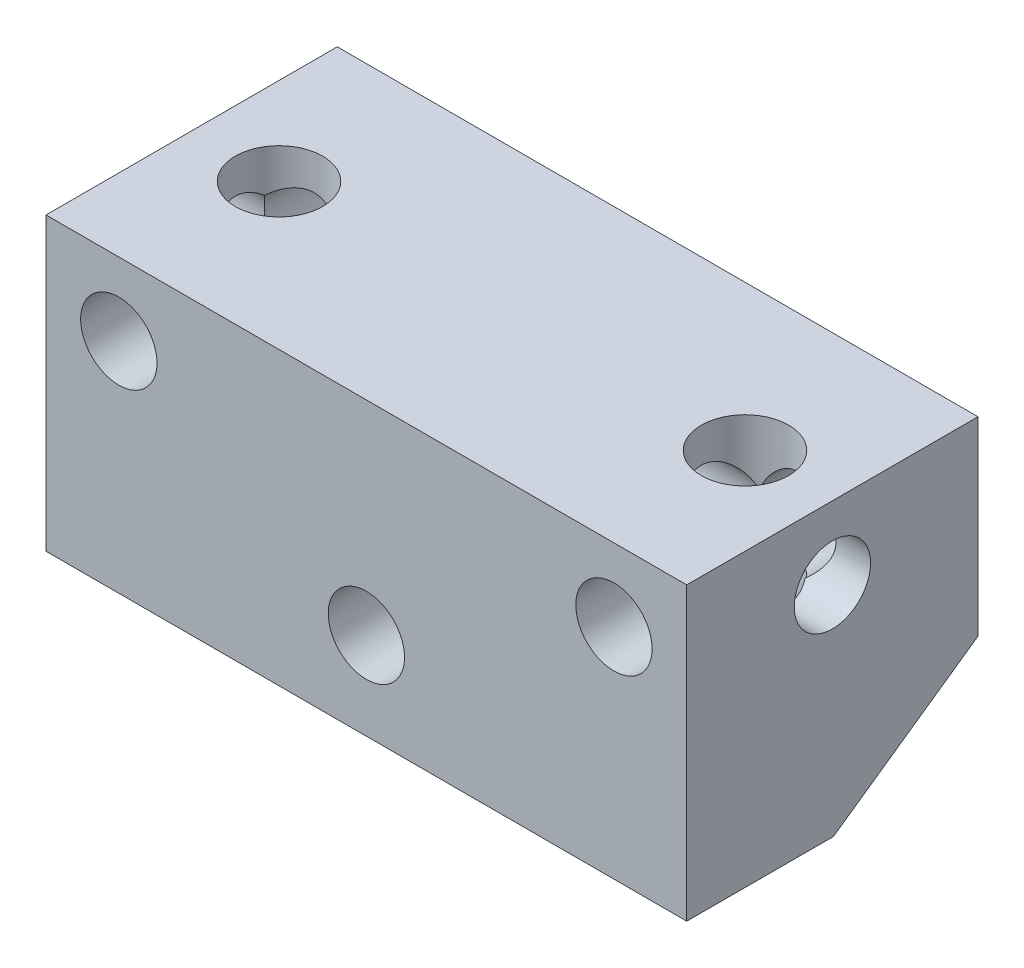
SolidWorks part; units mm, degrees
ref_plane "Front Plane" through (0, 0, 0) normal (0, 0, 1) x (1, 0, 0)
ref_plane "Top Plane" through (0, 0, 0) normal (0, 1, 0) x (1, 0, 0)
ref_plane "Right Plane" through (0, 0, 0) normal (1, 0, 0) x (0, 0, -1)
ref_plane "Plane1" through (11, 0, 0) normal (1, 0, 0) x (0, 0, -1)
sketch "Sketch1" plane through (11, 0, 0) normal (1, 0, 0) x (0, 0, -1)
  line L0 (-4.9626, -10) -> (0, -6.5252)
  line L1 (0, -6.5252) -> (0, 0)
  line L2 (0, 0) -> (-10, 0)
  line L3 (-10, 0) -> (-10, -10)
  line L4 (-10, -10) -> (-4.9626, -10)
extrude "Boss-Extrude1" add sketch "Sketch1" against normal blind 22
ref_plane "Plane2" through (0, -3.8559, 5.5068) normal (0, -0.5736, 0.8192) x (1, 0, 0)
sketch "Sketch2" plane through (0, -3.8559, 5.5068) normal (0, -0.5736, 0.8192) x (1, 0, 0)
  line L0 (3.175, 1.6549) -> (0, 1.6549)
  line L1 (0, 1.6549) -> (0, -5.3451)
  line L2 (0, -5.3451) -> (3.175, -5.3451)
  line L3 (3.175, -5.3451) -> (3.175, 1.6549)
  line L4 (0, 1.6549) -> (0, -5.3451) construction
revolve "Cut-Revolve1" cut sketch "Sketch2" angle 360 about L4
ref_plane "Plane3" through (0, -7, 0) normal (0, 1, 0) x (1, 0, 0)
sketch "Sketch3" plane through (0, -7, 0) normal (0, 1, 0) x (1, 0, 0)
  line L0 (1.3105, -6.2636) -> (0, -6.2636)
  line L1 (0, -6.2636) -> (0, -10)
  line L2 (0, -10) -> (1.3105, -10)
  line L3 (1.3105, -10) -> (1.3105, -6.2636)
  line L4 (0, -6.2636) -> (0, -10) construction
revolve "Cut-Revolve2" cut sketch "Sketch3" angle 360 about L4
ref_plane "Plane4" through (0, -2.5, 0) normal (0, 1, 0) x (1, 0, 0)
sketch "Sketch4" plane through (0, -2.5, 0) normal (0, 1, 0) x (1, 0, 0)
  line L0 (-7.1895, 0) -> (-8.5, 0)
  line L1 (-8.5, 0) -> (-8.5, -10)
  line L2 (-8.5, -10) -> (-7.1895, -10)
  line L3 (-7.1895, -10) -> (-7.1895, -2)
  line L4 (-7.1895, -2) -> (-7.1895, 0)
  line L5 (-8.5, 0) -> (-8.5, -10) construction
revolve "Cut-Revolve3" cut sketch "Sketch4" angle 360 about L5
sketch "Sketch5" plane through (0, -2.5, 0) normal (0, 1, 0) x (1, 0, 0)
  line L0 (9.8105, 0) -> (8.5, 0)
  line L1 (8.5, 0) -> (8.5, -10)
  line L2 (8.5, -10) -> (9.8105, -10)
  line L3 (9.8105, -10) -> (9.8105, -2)
  line L4 (9.8105, -2) -> (9.8105, 0)
  line L5 (8.5, 0) -> (8.5, -10) construction
revolve "Cut-Revolve4" cut sketch "Sketch5" angle 360 about L5
hole_wizard "Ø3.0 (3) Diameter Hole1" positions "Sketch7" profile "Sketch6" hole size "Ø3.0" standard "ANSI Metric"
sketch "Sketch7" plane through (0, 0, 0) normal (0, 1, 0) x (1, 0, 0)
  point P0 (8, -5)
  point P1 (-8, -5)
sketch "Sketch6" plane through (8, 0, 5) normal (1, 0, 0) x (0, 0, 1)
  line L0 (0, 0) -> (0, 10)
  line L1 (0, 10) -> (1.5, 10)
  line L2 (1.5, 10) -> (1.5, 0)
  line L5 (1.5, 0) -> (0, 0)
  line L11 (0, -6.35) -> (0, 107.95) construction
  dimension "Thru Hole Dia." = 3
  dimension "Thru Hole Depth" = 10
hole_wizard "Hole1" positions "Sketch9" profile "Sketch8" legacy
sketch "Sketch9" plane through (11, 0, 0) normal (1, 0, 0) x (0, 0, -1)
  point P0 (-5, -2.5)
sketch "Sketch8" plane through (11, -2.5, 5) normal (0, 1, 0) x (0, 0, -1)
  line L0 (0, 0) -> (0, 23.7192)
  line L1 (0, 23.7192) -> (1.3105, 23.7192)
  line L2 (1.3105, 23.7192) -> (1.3105, 0)
  line L3 (1.3105, 0) -> (0, 0)
  line L4 (0, 110) -> (0, -10) construction
  dimension "Diameter" = 2.621
  dimension "Depth" = 23.7192
